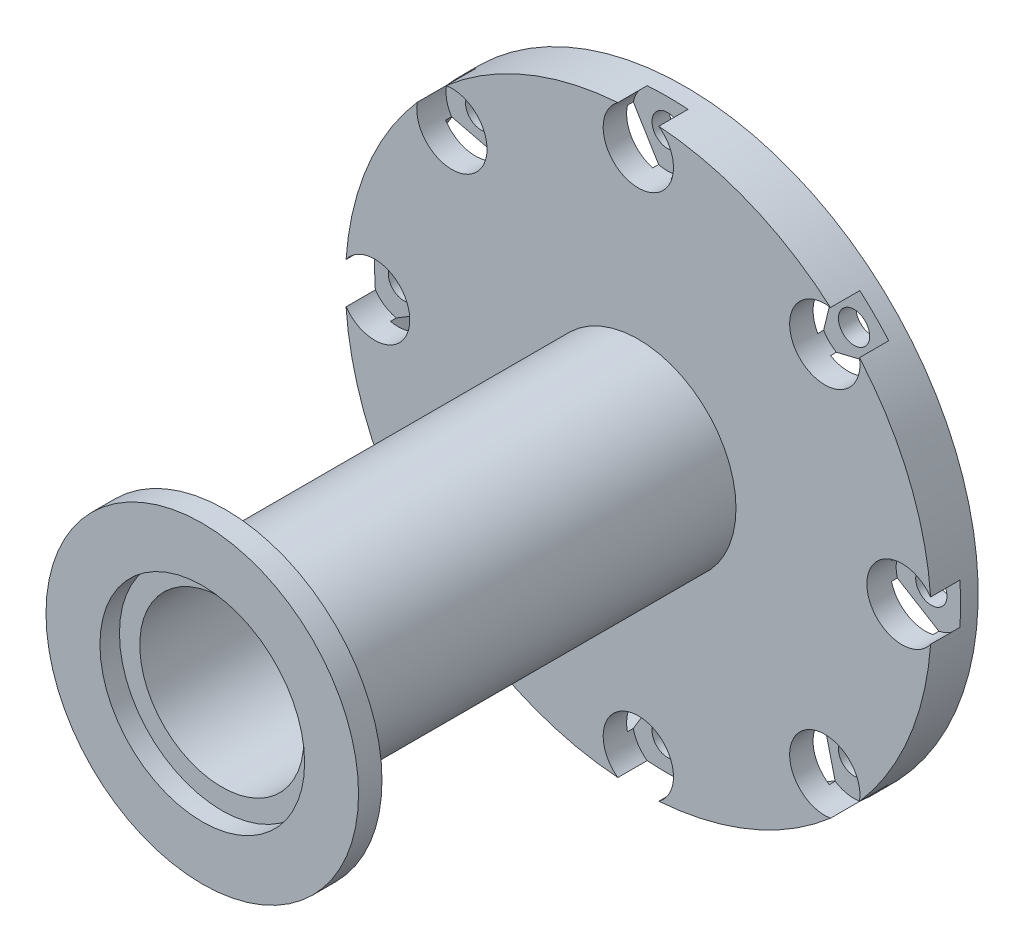
SolidWorks part; units mm, degrees
material "AISI 304"
ref_plane "Front Plane" through (0, 0, 0) normal (0, 0, 1) x (1, 0, 0)
ref_plane "Top Plane" through (0, 0, 0) normal (0, 1, 0) x (1, 0, 0)
ref_plane "Right Plane" through (0, 0, 0) normal (1, 0, 0) x (0, 0, -1)
sketch "Sketch1" plane through (0, 0, 0) normal (0, 0, 1) x (1, 0, 0)
  circle A0 centre (0, 0) radius 20.71 construction
  circle A1 centre (0, 0) radius 20.71
  circle A2 centre (0, 0) radius 19.21 construction
  circle A3 centre (0, 0) radius 19.21
  circle A5 centre (0, 0) radius 37.5 construction
  circle A6 centre (23.8649, -23.8649) radius 2 construction
  circle A7 centre (33.75, 0) radius 2 construction
  circle A8 centre (-23.8649, 23.8649) radius 2 construction
  circle A9 centre (-33.75, 0) radius 2 construction
  circle A10 centre (-23.8649, -23.8649) radius 2 construction
  circle A11 centre (0, -33.75) radius 2 construction
  circle A12 centre (23.8649, -23.8649) radius 2
  circle A13 centre (33.75, 0) radius 2
  circle A14 centre (-23.8649, 23.8649) radius 2
  circle A15 centre (-33.75, 0) radius 2
  circle A16 centre (-23.8649, -23.8649) radius 2
  circle A17 centre (0, -33.75) radius 2
  circle A18 centre (0, 0) radius 37.5
sketch "Sketch2" plane through (0, 0, 0) normal (0, 0, 1) x (1, 0, 0)
  circle A1 centre (0, 0) radius 37.5 construction
  circle A2 centre (0, 0) radius 5.35 construction
  circle A3 centre (0, 0) radius 5.35
  circle A4 centre (0, 0) radius 37.5
extrude "Boss-Extrude2" add sketch "Sketch2" along normal blind 8
sketch "Sketch3" plane through (0, 0, 0) normal (0, 0, 1) x (1, 0, 0)
  circle A0 centre (0, 0) radius 20.71 construction
  circle A1 centre (0, 0) radius 20.71
  circle A2 centre (0, 0) radius 19.21 construction
  circle A3 centre (0, 0) radius 19.21 construction
sketch "Sketch14" plane through (0, 0, 0) normal (0, 0, 1) x (1, 0, 0)
  circle A7 centre (0, 33.75) radius 2
  circle A8 centre (0, 33.75) radius 2
  circle A9 centre (-23.8649, 23.8649) radius 2
  circle A10 centre (-23.8649, 23.8649) radius 2
  circle A11 centre (-33.75, 0) radius 2
  circle A12 centre (-33.75, 0) radius 2
  circle A13 centre (-23.8649, -23.8649) radius 2
  circle A14 centre (-23.8649, -23.8649) radius 2
  circle A15 centre (0, -33.75) radius 2
  circle A16 centre (0, -33.75) radius 2
  circle A17 centre (23.8649, -23.8649) radius 2
  circle A18 centre (23.8649, -23.8649) radius 2
  circle A19 centre (33.75, 0) radius 2
  circle A20 centre (33.75, 0) radius 2
  circle A21 centre (23.8649, 23.8649) radius 2
  circle A22 centre (23.8649, 23.8649) radius 2
  dimension "D1" = 0
  dimension "D2" = 0
  dimension "D3" = 0
  dimension "D4" = 0
  dimension "D5" = 0
  dimension "D6" = 0
  dimension "D7" = 0
  dimension "D8" = 0
extrude "Cut-Extrude6" cut sketch "Sketch14" along normal through all
extrude "Cut-Extrude2" cut sketch "Sketch3" along normal blind 6.5
sketch "Sketch6" plane through (0, 0, 8) normal (0, 0, 1) x (1, 0, 0)
  circle A1 centre (0, 0) radius 10.45
  circle A2 centre (0, 0) radius 5.35 construction
  circle A3 centre (0, 0) radius 6.45
  dimension "D1" = 1.1
  dimension "D2" = 4
extrude "Boss-Extrude3" [suppressed] add sketch "Sketch6" along normal blind 40
sketch "Sketch7" plane through (0, 0, 8) normal (0, 0, 1) x (1, 0, 0)
  circle A0 centre (0, 0) radius 12.5
  circle A1 centre (0, 0) radius 10.5
  dimension "D1" = 25
  dimension "D2" = 2
extrude "Boss-Extrude4" add sketch "Sketch7" along normal blind 50.8
sketch "Sketch10" plane through (0, 0, 58.8) normal (0, 0, 1) x (1, 0, 0)
  circle A0 centre (0, 0) radius 12.5 construction
  circle A1 centre (0, 0) radius 12.5
extrude "Boss-Extrude5" add sketch "Sketch10" along normal blind 2.01 draft 75 draft outward yes
sketch "Sketch11" plane through (0, 0, 60.81) normal (0, 0, 1) x (1, 0, 0)
  circle A1 centre (0, 0) radius 10.5 construction
  circle A2 centre (0, 0) radius 10.5
extrude "Cut-Extrude3" cut sketch "Sketch11" against normal through all
sketch "Sketch12" plane through (0, 0, 60.81) normal (0, 0, 1) x (1, 0, 0)
  circle A0 centre (0, 0) radius 10.5 construction
  circle A1 centre (0, 0) radius 20.0014 construction
  circle A2 centre (0, 0) radius 10.5
  circle A3 centre (0, 0) radius 20.0014
extrude "Boss-Extrude6" add sketch "Sketch12" along normal blind 3
sketch "Sketch13" plane through (0, 0, 63.81) normal (0, 0, 1) x (1, 0, 0)
  circle A0 centre (0, 0) radius 13.1
  dimension "D1" = 26.2
extrude "Cut-Extrude4" cut sketch "Sketch13" against normal blind 2.5
chamfer "Chamfer1" [suppressed] distance 10 angle 45
chamfer "Chamfer2" [suppressed] distance 10 angle 45
sketch "Sketch15" [suppressed] plane through (0, 0, 48) normal (0, 0, 1) x (1, 0, 0)
  circle A2 centre (0, 0) radius 7.35
  circle A3 centre (0, 0) radius 7.35
  dimension "D1" = 2
extrude "Cut-Extrude7" [suppressed] cut sketch "Sketch15" against normal blind 10
sketch "Sketch17" plane through (0, 0, 8) normal (0, 0, 1) x (1, 0, 0)
  circle A1 centre (-23.8649, 23.8649) radius 4.5
  circle A2 centre (-33.75, 0) radius 4.5
  circle A3 centre (-33.75, 0) radius 4.5
  circle A4 centre (0, 33.75) radius 4.5
  circle A5 centre (23.8649, 23.8649) radius 4.5
  circle A6 centre (33.75, 0) radius 4.5
  circle A7 centre (23.8649, -23.8649) radius 4.5
  circle A8 centre (0, -33.75) radius 4.5
  circle A9 centre (-23.8649, -23.8649) radius 4.5
  point P19 (0, 0)
  dimension "D1" = 2.5
  dimension "D2" = 8
extrude "Cut-Extrude8" cut sketch "Sketch17" against normal blind 3.75
sketch "Sketch18" plane through (0, 0, 0) normal (0, 0, -1) x (-1, 0, 0)
  circle A0 centre (0, 0) radius 37.5 construction
  circle A1 centre (0, 0) radius 37.5
extrude "Cut-Extrude9" cut sketch "Sketch18" against normal blind 2
sketch "Sketch19" plane through (0, 0, 2) normal (0, 0, -1) x (-1, 0, 0)
  circle A3 centre (0, 0) radius 27.5
  circle A4 centre (0, 0) radius 27.5
  dimension "D1" = 10
extrude "Cut-Extrude10" cut sketch "Sketch19" against normal blind 3
sketch "Sketch21" plane through (0, 0, 2) normal (0, 0, -1) x (-1, 0, 0)
  line L0 (-27.5, 0) -> (-35.1908, 4.6749)
  line L1 (-27.5, 0) -> (-35.19, -4.6809)
  line L2 (-19.4454, 19.4454) -> (-21.578, 28.1893)
  line L3 (-19.4454, 19.4454) -> (-28.193, 21.5732)
  line L4 (0, 27.5) -> (4.6749, 35.1908)
  line L5 (0, 27.5) -> (-4.6809, 35.19)
  line L6 (19.4454, 19.4454) -> (28.1893, 21.578)
  line L7 (19.4454, 19.4454) -> (21.5732, 28.193)
  line L8 (27.5, 0) -> (35.1908, -4.6749)
  line L9 (27.5, 0) -> (35.19, 4.6809)
  line L10 (19.4454, -19.4454) -> (21.578, -28.1893)
  line L11 (19.4454, -19.4454) -> (28.193, -21.5732)
  line L12 (0, -27.5) -> (-4.6749, -35.1908)
  line L13 (0, -27.5) -> (4.6809, -35.19)
  line L14 (-19.4454, -19.4454) -> (-28.1893, -21.578)
  line L15 (-19.4454, -19.4454) -> (-21.5732, -28.193)
  arc A0 (-28.193, 21.5732) -> (-35.1908, 4.6749) centre (0, 0) ccw
  circle A1 centre (0, 0) radius 27.5 construction
  circle A2 centre (0, 0) radius 35.5
  arc A3 (-35.19, -4.6809) -> (-28.1893, -21.578) centre (0, 0) ccw
  circle A4 centre (0, 0) radius 27.5
  arc A5 (-21.5732, -28.193) -> (-4.6749, -35.1908) centre (0, 0) ccw
  arc A6 (4.6809, -35.19) -> (21.578, -28.1893) centre (0, 0) ccw
  arc A7 (28.193, -21.5732) -> (35.1908, -4.6749) centre (0, 0) ccw
  arc A8 (35.19, 4.6809) -> (28.1893, 21.578) centre (0, 0) ccw
  arc A9 (21.5732, 28.193) -> (4.6749, 35.1908) centre (0, 0) ccw
  arc A10 (-4.6809, 35.19) -> (-21.578, 28.1893) centre (0, 0) ccw
  point P31 (0, 0)
  circle M2 centre (0, 0) radius 27.5
  dimension "D1" = 2
  dimension "D2" = 8
extrude "Cut-Extrude11" cut sketch "Sketch21" against normal blind 3 contours L1 A3 L14 M2 | L3 A0 L0 M2 | L5 A10 L2 M2 | L7 A9 L4 M2 | L9 A8 L6 M2 | L11 A7 L8 M2 | L13 A6 L10 M2 | L15 A5 L12 M2
